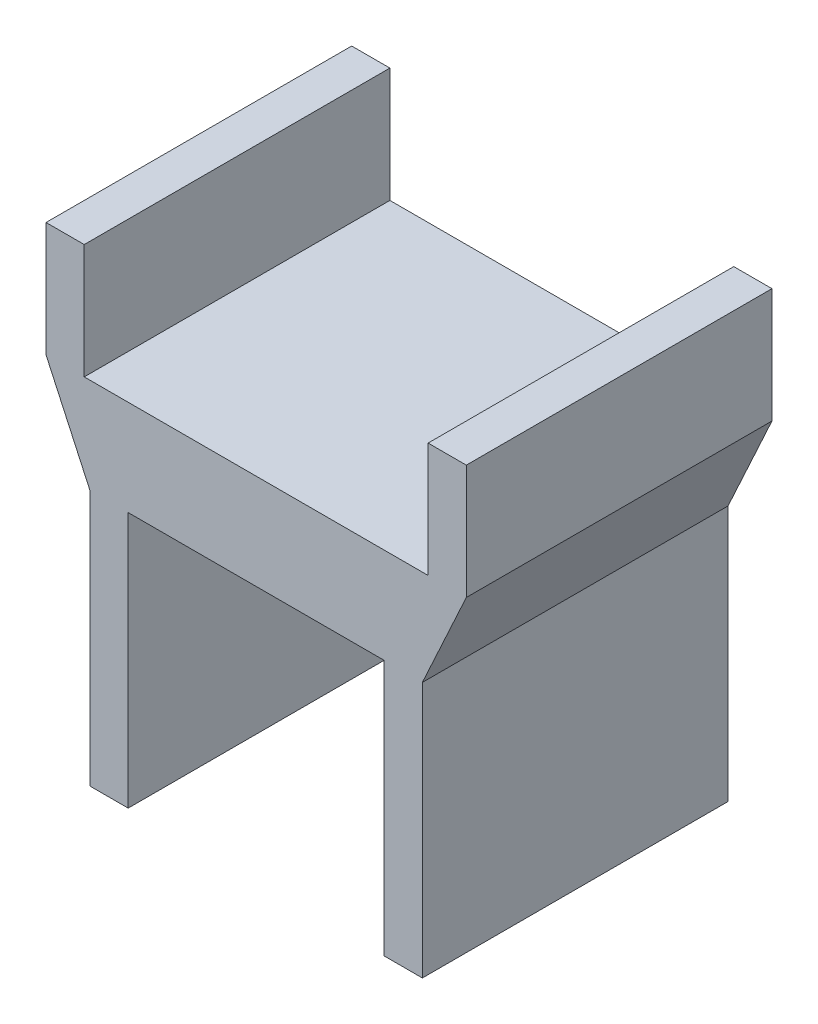
SolidWorks part; units mm, degrees
ref_plane "Alzado" through (0, 0, 0) normal (0, 0, 1) x (1, 0, 0)
ref_plane "Planta" through (0, 0, 0) normal (0, 1, 0) x (1, 0, 0)
ref_plane "Vista lateral" through (0, 0, 0) normal (1, 0, 0) x (0, 0, -1)
sketch "Croquis1" plane through (0, 0, 0) normal (0, 0, 1) x (1, 0, 0)
  line L8 (6.7, 5) -> (15.7, 5)
  line L9 (0, 0) -> (13.4, 0)
  line L14 (0, 0) -> (0, -13.4)
  line L15 (0, -13.4) -> (13.4, -13.4)
  line L16 (13.4, 0) -> (13.4, -13.4)
  line L21 (13.4, -13.4) -> (15.4, -13.4)
  line L22 (13.4, -13.4) -> (13.4, 0)
  line L23 (13.4, 0) -> (15.4, 0)
  line L27 (15.4, -13.4) -> (15.4, 0)
  line L30 (0, 0) -> (-2, 0)
  line L31 (0, 0) -> (0, -13.4)
  line L32 (0, -13.4) -> (-2, -13.4)
  line L33 (-2, 0) -> (-2, -13.4)
  line L34 (-2, 0) -> (15.4, 0)
  line L35 (-2, 0) -> (-2, 5)
  line L36 (-2, 5) -> (15.4, 5)
  line L37 (15.4, 0) -> (15.4, 5)
  line L38 (6.7, 5) -> (-2.3, 5)
  line L39 (17.7, 5) -> (15.4, 0)
  line L40 (-2.3, 5) -> (15.7, 5)
  line L41 (-2.3, 5) -> (-2.3, 11)
  line L42 (-2.3, 11) -> (15.7, 11)
  line L43 (15.7, 5) -> (15.7, 11)
  line L44 (-2.3, 5) -> (-4.3, 5)
  line L45 (-2.3, 5) -> (-2.3, 11)
  line L46 (-2.3, 11) -> (-4.3, 11)
  line L47 (-4.3, 5) -> (-4.3, 11)
  line L48 (15.7, 5) -> (17.7, 5)
  line L49 (15.7, 5) -> (15.7, 11)
  line L50 (15.7, 11) -> (17.7, 11)
  line L51 (17.7, 5) -> (17.7, 11)
  line L52 (-4.3, 5) -> (-2, 0)
  dimension "D1" = 13.4
  dimension "D2" = 13.4
  dimension "D4" = 2
  dimension "D7" = 9
  dimension "D10" = 2
  dimension "D3" = 2
  dimension "D5" = 5
  dimension "D6" = 9
  dimension "D8" = 6
  dimension "D9" = 2
extrude "Saliente-Extruir1" add sketch "Croquis1" along normal blind 16 contours L30 L33 L32 L14 | L23 L37 L8 L36 L35 L30 L9 | L21 L27 L23 L16 | L48 L8 L37 L39 | L48 L51 L50 L43 | L44 L52 L35 L38 | L47 L44 L41 L46
